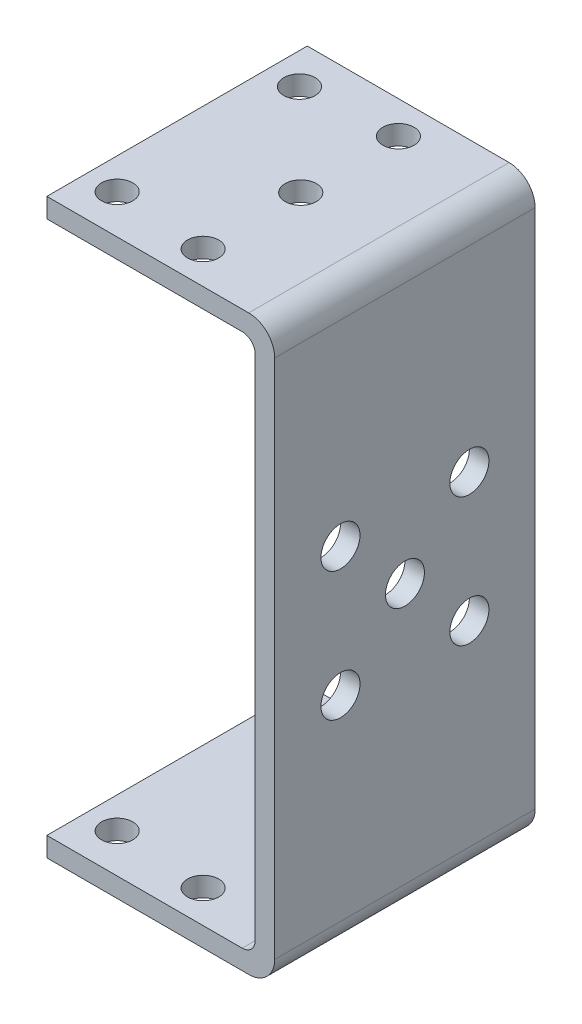
SolidWorks part; units mm, degrees
ref_plane "前视基准面" through (0, 0, 0) normal (0, 0, 1) x (1, 0, 0)
ref_plane "上视基准面" through (0, 0, 0) normal (0, 1, 0) x (1, 0, 0)
ref_plane "右视基准面" through (0, 0, 0) normal (1, 0, 0) x (0, 0, -1)
other "Configuration Table"
sketch "草图1" plane through (0, 0, 0) normal (0, 1, 0) x (1, 0, 0)
  line L0 (0, -10) -> (12, -10) construction
  line L1 (0, 0) -> (12, 0)
  line L2 (0, 0) -> (0, -20)
  line L3 (0, -20) -> (12, -20)
  line L4 (12, 0) -> (12, -20)
  line L5 (9.5, -2.5) -> (9.5, -17.5) construction
  circle A0 centre (2.4, -3) radius 1.2
  circle A1 centre (9.5, -2.5) radius 1.2
  circle A2 centre (2.4, -17) radius 1.2
  circle A3 centre (9.5, -10) radius 1.2
  circle A4 centre (9.5, -17.5) radius 1.2
  dimension "D3" = 2.4
  dimension "D1" = 12
  dimension "D2" = 20
  dimension "D4" = 14
  dimension "D5" = 2.4
  dimension "D6" = 9.5
  dimension "D7" = 7.5
  dimension "D8" = 7.5
extrude "凸台-拉伸1" add sketch "草图1" along normal blind 1.5
sketch "草图2" plane through (0, 0, 0) normal (0, 0, -1) x (-1, 0, 0)
  line L0 (-12, 1.5) -> (-17.5, 1.5)
  line L1 (-17.5, 1.5) -> (-17.5, -20.5)
  line L2 (-17.5, -20.5) -> (-16, -20.5)
  line L3 (-16, -20.5) -> (-16, 0)
  line L4 (-16, 0) -> (-12, 0)
  line L5 (-12, 1.5) -> (-12, 0) construction
  line L6 (-12, 1.5) -> (-12, -0.2354)
  line M6 (-12, 1.5) -> (-12, 0)
  dimension "D1" = 1.5
  dimension "D2" = 4
  dimension "D3" = 20.5
extrude "凸台-拉伸2" add sketch "草图2" against normal blind 20 contours L3 L4 L0 L1 L2 M6
mirror "镜向2" about plane through (0, -20.5, 20) normal (0, -1, 0) of bodies 107
sketch "草图3" plane through (17.5, 0, 0) normal (1, 0, 0) x (0, 0, -1)
  line L0 (-20, -20.5) -> (0, -20.5) construction
  line L1 (-20, 1.5) -> (-20, -42.5) construction
  line L2 (0, 1.5) -> (0, -42.5) construction
  line L3 (-14.9497, -15.5503) -> (-10, -20.5) construction
  circle A0 centre (-10, -20.5) radius 1.5
  circle A2 centre (-14.9497, -15.5503) radius 1.5
  circle A3 centre (-5.0503, -15.5503) radius 1.5
  circle A4 centre (-5.0503, -25.4497) radius 1.5
  circle A5 centre (-14.9497, -25.4497) radius 1.5
  point P10 (-10, -20.5)
  point P19 (-10, -20.5)
  dimension "D2" = 3
  dimension "D4" = 3
  dimension "D1" = 7
  dimension "D3" = 45
  dimension "D5" = 4
extrude "切除-拉伸1" cut sketch "草图3" against normal blind 10
fillet "圆角1" radius 2 2 edges at (17.5, 1.5, 10) (17.5, -42.5, 10)
fillet "圆角2" radius 1 2 edges at (16, 0, 10) (16, -41, 10)
